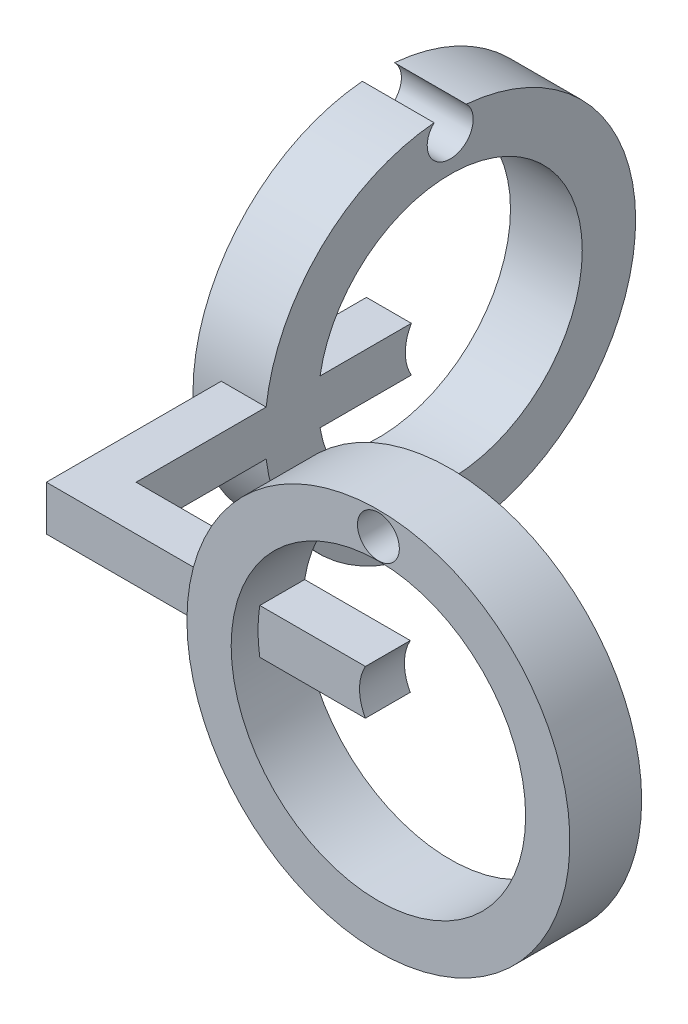
SolidWorks part; units mm, degrees
ref_plane "Front Plane" through (0, 0, 0) normal (0, 0, 1) x (1, 0, 0)
ref_plane "Top Plane" through (0, 0, 0) normal (0, 1, 0) x (1, 0, 0)
ref_plane "Right Plane" through (0, 0, 0) normal (1, 0, 0) x (0, 0, -1)
sketch "Sketch1" plane through (0, 0, 0) normal (0, 1, 0) x (1, 0, 0)
  line L0 (0, 0) -> (0, 70)
  line L1 (0, 70) -> (-10, 70)
  line L2 (-10, 70) -> (-10, -10)
  line L3 (-10, -10) -> (70, -10)
  line L4 (70, -10) -> (70, 0)
  line L5 (70, 0) -> (0, 0)
  dimension "D1" = 10
  dimension "D2" = 10
  dimension "D3" = 70
  dimension "D4" = 70
extrude "Boss-Extrude1" add sketch "Sketch1" along normal blind 10
sketch "Sketch3" plane through (0, 0, 10) normal (0, 0, 1) x (1, 0, 0)
  line L0 (70, 10) -> (70, 0) construction
  circle A0 centre (65, 5) radius 5
  point P5 (70, 5)
  dimension "D1" = 10
  dimension "D2" = 5
extrude "Boss-Extrude2" add sketch "Sketch3" along normal blind 5
sketch "Sketch4" plane through (0, 0, 15) normal (0, 0, 1) x (1, 0, 0)
  line L0 (70, 10) -> (70, 0) construction
  line L1 (68.2727, 5.5) -> (55.4303, 5.5)
  line L2 (68.2727, 5.5) -> (68.2727, 4.5)
  line L3 (68.2727, 4.5) -> (55.4303, 4.5)
  line L4 (55.4303, 5.5) -> (55.4303, 4.5)
  point P6 (70, 5)
  point P7 (55.4303, 5)
  dimension "D1" = 1
  dimension "D2" = 12.8424
extrude "Cut-Extrude1" cut sketch "Sketch4" against normal blind 5
sketch "Sketch5" plane through (-10, 0, 0) normal (-1, 0, 0) x (0, 0, 1)
  line L0 (-70, 10) -> (-70, 0) construction
  circle A0 centre (-44.3546, 5) radius 3.4181
  point P5 (-70, 5)
extrude "Boss-Extrude3" add sketch "Sketch5" along normal blind 5
sketch "Sketch6" plane through (-15, 0, 0) normal (-1, 0, 0) x (0, 0, 1)
  line L0 (10, 0) -> (10, 5) construction
  line L1 (-54.6363, 3) -> (-45.2893, 3)
  line L2 (-54.6363, 3) -> (-54.6363, 2)
  line L3 (-54.6363, 2) -> (-45.2893, 2)
  line L4 (-45.2893, 3) -> (-45.2893, 2)
  point P4 (-45.2893, 2.5)
  point P7 (10, 2.5)
  dimension "D1" = 1
  dimension "D2" = 9.347
extrude "Cut-Extrude2" cut sketch "Sketch6" against normal blind 5
sketch "Sketch7" plane through (0, 0, 0) normal (0, 0, -1) x (-1, 0, 0)
  line L0 (-70, 10) -> (-70, 0) construction
  circle A0 centre (-70, 5) radius 42.6681
  circle A1 centre (-70, 5) radius 32.8121
extrude "Boss-Extrude4" add sketch "Sketch7" against normal blind 16
sketch "Sketch8" plane through (0, 0, 0) normal (0, 0, -1) x (-1, 0, 0)
  circle A0 centre (-70, 5) radius 10.2043
extrude "Cut-Extrude3" cut sketch "Sketch8" against normal blind 16
sketch "Sketch9" plane through (0, 0, 0) normal (1, 0, 0) x (0, 0, -1)
  line L0 (70, 10) -> (70, 0) construction
  circle A0 centre (70, 5) radius 41.3208
  circle A1 centre (70, 5) radius 29.4318
  point P6 (70, 5)
extrude "Boss-Extrude5" add sketch "Sketch9" against normal blind 16
sketch "Sketch10" plane through (0, 0, 0) normal (1, 0, 0) x (0, 0, -1)
  circle A0 centre (70, 5) radius 10.0021
extrude "Cut-Extrude4" cut sketch "Sketch10" against normal blind 16
sketch "Sketch11" plane through (0, 0, 0) normal (1, 0, 0) x (0, 0, -1)
  circle A0 centre (70, 5) radius 37.5
  circle A1 centre (70, 42.5) radius 5.1255
  arc M2 (28.9828, 0) -> (28.9828, 10) centre (70, 5) ccw
  dimension "D1" = 75
extrude "Cut-Extrude5" cut sketch "Sketch11" against normal blind 16 contours A1 A0 M2 | A0 A1
sketch "Sketch12" plane through (0, 0, 0) normal (0, 0, -1) x (-1, 0, 0)
  circle A0 centre (-70, 5) radius 37.5
  circle A1 centre (-70, 42.5) radius 4.6621
  dimension "D1" = 75
extrude "Cut-Extrude6" cut sketch "Sketch12" against normal blind 16 contours A0 A1 | A0 A1
